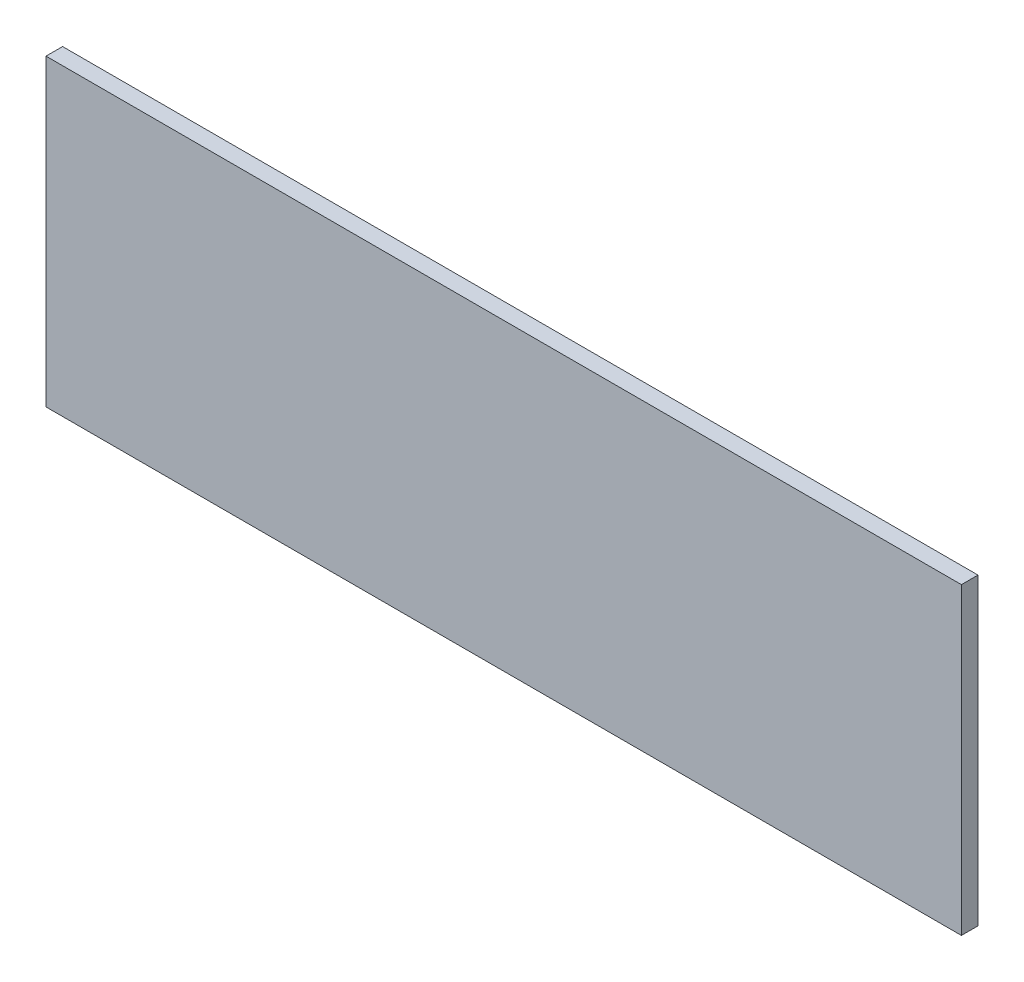
SolidWorks part; units mm, degrees
ref_plane "Front Plane" through (0, 0, 0) normal (0, 0, 1) x (1, 0, 0)
ref_plane "Top Plane" through (0, 0, 0) normal (0, 1, 0) x (1, 0, 0)
ref_plane "Right Plane" through (0, 0, 0) normal (1, 0, 0) x (0, 0, -1)
sketch "Sketch1" plane through (0, 0, 0) normal (0, 0, 1) x (1, 0, 0)
  line L1 (0, 0) -> (254, 0)
  line L2 (0, 0) -> (0, 84.3)
  line L3 (0, 84.3) -> (254, 84.3)
  line L4 (254, 0) -> (254, 84.3)
  dimension "D1" = 254
  dimension "D2" = 84.3
extrude "Boss-Extrude1" add sketch "Sketch1" along normal blind 4.6
equation "\"MDF\"= 4.8mm"
equation "\"Foamcore\"= 4.6mm"
equation "\"GMaterial\"= \"MDF\""
equation "\"PCB\" = 1.6mm"
equation "\"BaseWidth\" = 10in"
equation "\"SkidLength\" = 1in"
equation "\"SkidClearance\" = 0.4in"
equation "\"MotorMountLength\" = 2in"
equation "\"MotorMountWidth\" = \"GMaterial\""
equation "\"MotorMountHeight\" = 2.25in"
equation "\"UnoStackWidth\" = 77.4mm"
equation "\"UnoStackLength\" = 79.8mm"
equation "\"UnoStackHeight\" = 34.2mm"
equation "\"TallHexRiserHeight\" = 22.2mm"
equation "\"PingPongBallSize\" = 40mm"
equation "\"BarrelLength\" = 9in"
equation "\"BarrelSize\" = \"PingPongBallSize\""
equation "\"PlatformLength\" = 4in"
equation "\"PlatformWidth\" = 6in"
equation "\"WheelDiameter\"=2.99213"
equation "\"ServoMountHeight\"=2.49223"
equation "\"ServoGearHeight\" = 0.95330261in"
equation "\"ServoMountLength\"= 1.53774"
equation "\"PivotHoleRadius\"= 0.616358"
equation "\"PlatformMountHeight\" = 3.19"
equation "\"TensionOffSet\"= .3mm"
equation "\"MotorMountWedge\"=0.333333"
equation "\"LaserCutterOffset\"= .3mm"
equation "\"BumperWidth\"=11"
equation "\"PitcherWheelCompression\" = 2.5mm"
equation "\"BarrelToHopperDistance\" = 0.5405in"
equation "\"PitchingWheelWidth\" = 26.2mm"
equation "\"PitchingWheelDiameter\" = 65.5mm"
equation "\"PitchingWheelMountOffset\" = 8.4mm"
equation "\"PitchingWheelInnerDiameter\" = 45.5mm"
equation "\"PitchingWheelBoltShoulder\" = 4.5mm"
equation "\"BrassCouplingLength\" = 18mm"
equation "\"PitchingMotorHeight\" = 57.0mm"
equation "\"PitchingMotorShaftTopHeight\" = \"PitchingMotorHeight\" - 44.1mm"
equation "\"PitchingMotorBodyHeight\" = 38mm"
equation "\"PitchingMotorTopShoulderHeight\" = 40.6mm - \"PitchingMotorBodyHeight\" "
equation "\"PitchingMotorBottomShoulderHeight\" = 40.2mm - \"PitchingMotorBodyHeight\""
equation "\"PitchingMotorBottomShaftHeight\" = \"PitchingMotorHeight\" - \"PitchingMotorShaftTopHeight\" - \"PitchingMotorTopShoulderHeight\" - \"PitchingMotorBodyHeight\" - \"PitchingMotorBottomShoulderHeight\""
equation "\"PitchingMotorShaftDiameter\" = 2.2mm"
equation "\"PitchingMotorBodyDiameter\" = 27.4mm"
equation "\"PitchingMotorTopShoulderDiameter\" = 9.8mm"
equation "\"PitchingMotorBottomShoulderDiameter\" = 9.8mm"
equation "\"BrassCouplingHexSize\" = 12mm"
equation "\"BrassCouplingBoreSize\" = 3.17mm"
equation "\"PitchingMotorMountingHoleDistance\" = 16mm"
equation "\"Acrylic\" = 4.4mm"
equation "\"PitchingMotorDistance\" = \"PitchingWheelDiameter\" + \"PingPongBallSize\" - \"PitcherWheelCompression\"*2"
equation "\"PitchingMotorPlatformOffset\"=1"
equation "\"ServoPlatformOffset\"=1.64173"
equation "\"BallBearingDiameter\" = 22mm"
equation "\"BallBearingWidth\" = 9mm"
equation "\"BallBearingHexShoulder\" = 9mm - 5.9mm"
equation "\"BallBearingHexSize\" = .36in"
equation "\"PlatformMountFootLength\"=0.857143"
equation "\"WheelWidth\"= 26mm"
equation "\"ServoMountReductionBackHeight\"=2.25"
equation "\"PlatformBottomWidthThird\" =  0.857143in"
equation "\"PlatformMountBackReductionHeight\"= 2.5in"
equation "\"PlatformMountBackReductionWidth\"= 3/7in"
equation "\"PlatformMountFrontReductionWidth\" =  1.46226in"
equation "\"PlatformMountFrontReductionHeight\" = 2.5in"
equation "\"HopperLongWallLength\" = 8.646in"
equation "\"HopperShortWallLength\" = 0.9571in"
equation "\"HopperHeight\" = 3.50in - \"Foamcore\""
equation "\"HoperLongSlantLength\" = 7.064in"
equation "\"HopperBottomTemplateWidth\" = 8.03903165in"
equation "\"HopperBottomTemplateLength\" = 10.367854in"
equation "\"BeaconDiameter\" = 3.45in"
equation "\"HopperTopWidth\" = 11 - \"Foamcore\"*2 - \"BeaconDiameter\""
equation "\"D2@Sketch1\"=\"HopperHeight\""
equation "\"D1@Boss-Extrude1\"=\"Foamcore\""
